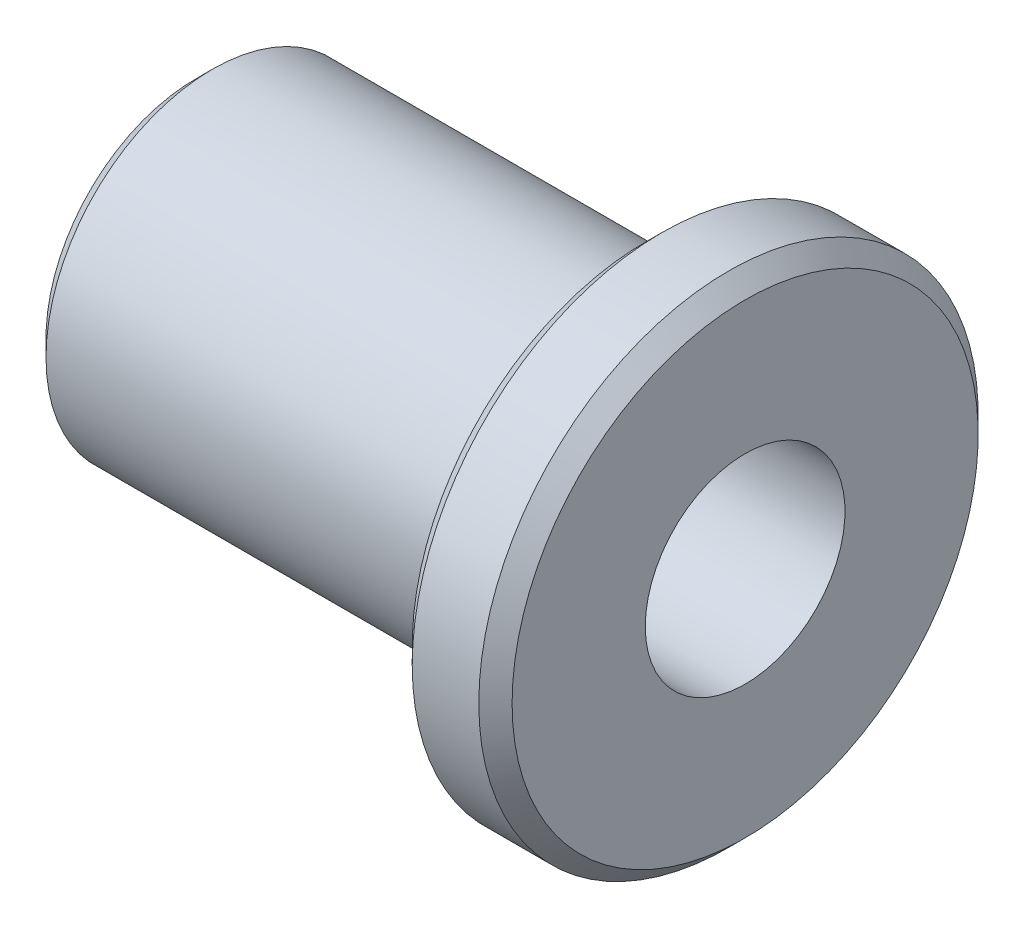
SolidWorks part; units mm, degrees
ref_plane "Plan1" through (0, 0, 0) normal (0, 0, 1) x (1, 0, 0)
ref_plane "Plan2" through (0, 0, 0) normal (0, 1, 0) x (1, 0, 0)
ref_plane "Plan3" through (0, 0, 0) normal (1, 0, 0) x (0, 0, -1)
sketch "Esquisse1" plane through (0, 0, 0) normal (0, 0, 1) x (1, 0, 0)
  line L0 (0, 0) -> (36.6906, 0) construction
  line L1 (0, 3) -> (0, 5)
  line L2 (0, 5) -> (13.5, 5)
  line L3 (13.5, 5) -> (13.5, 7.5)
  line L4 (13.5, 7.5) -> (16.5, 7.5)
  line L5 (16.5, 7.5) -> (16.5, 3)
  line L6 (16.5, 3) -> (0, 3)
  dimension "D1" = 3
  dimension "D2" = 7.5
  dimension "D3" = 5
  dimension "D4" = 3
  dimension "D5" = 13.5
revolve "Base-Révolution" add sketch "Esquisse1" angle 360 about L0
chamfer "Chanfrein1" distance 0.5 angle 45 4 edges at (16.5, 0, 7.5) (13.5, 0, 7.5) (0, 0, 5) (0, 0, 3)
